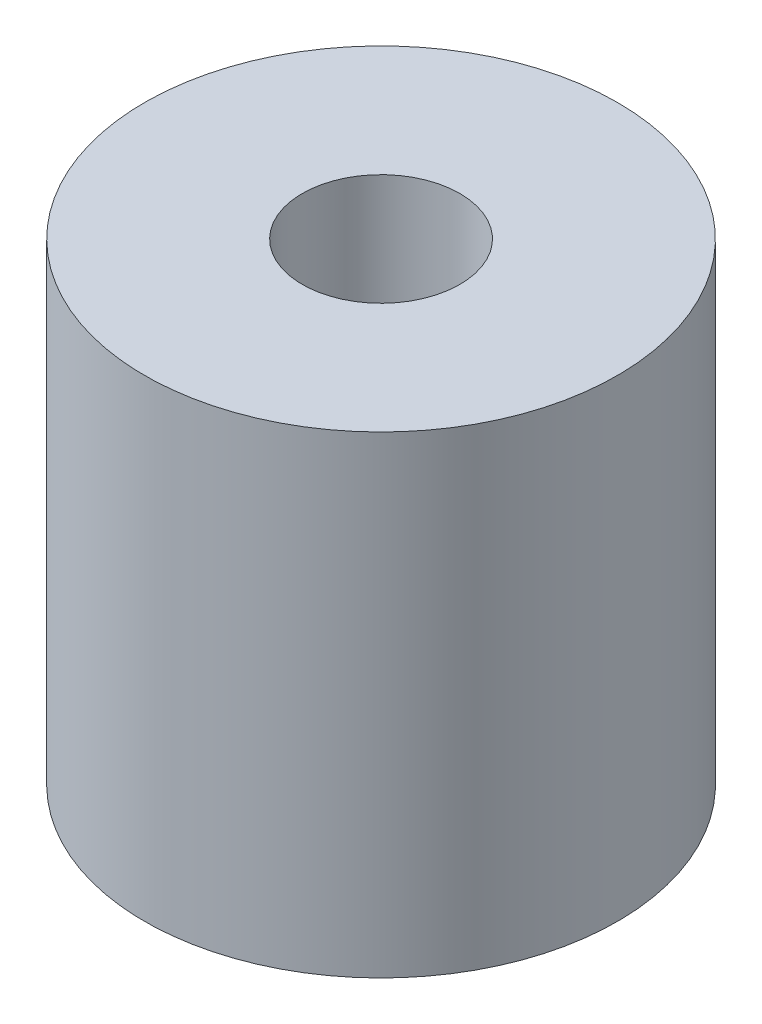
SolidWorks part; units mm, degrees
ref_plane "Front Plane" through (0, 0, 0) normal (0, 0, 1) x (1, 0, 0)
ref_plane "Top Plane" through (0, 0, 0) normal (0, 1, 0) x (1, 0, 0)
ref_plane "Right Plane" through (0, 0, 0) normal (1, 0, 0) x (0, 0, -1)
sketch "Sketch1" plane through (0, 0, 0) normal (0, 1, 0) x (1, 0, 0)
  circle A0 centre (0, 0) radius 0.7937
  circle A1 centre (0, 0) radius 2.3813
  dimension "D1" = 1.5875
  dimension "D2" = 4.7625
extrude "Boss-Extrude1" add sketch "Sketch1" along normal blind 4.7625
